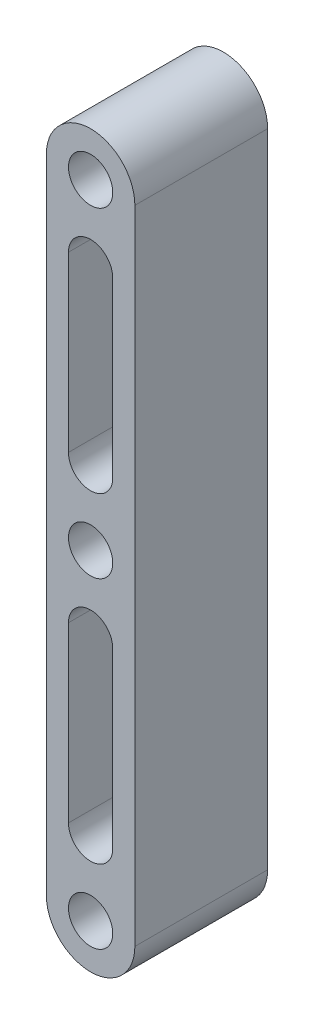
SolidWorks part; units mm, degrees
ref_plane "Front Plane" through (0, 0, 0) normal (0, 0, 1) x (1, 0, 0)
ref_plane "Top Plane" through (0, 0, 0) normal (0, 1, 0) x (1, 0, 0)
ref_plane "Right Plane" through (0, 0, 0) normal (1, 0, 0) x (0, 0, -1)
sketch "Sketch1" plane through (0, 0, 0) normal (0, 0, 1) x (1, 0, 0)
  line L0 (0, 0) -> (0, -87) construction
  line L1 (6, 0) -> (6, -87)
  line L2 (-6, 0) -> (-6, -87)
  line L3 (0, -10) -> (0, -33.5) construction
  line L4 (3, -10) -> (3, -33.5)
  line L5 (-3, -10) -> (-3, -33.5)
  line L6 (0, -53.5) -> (0, -77) construction
  line L7 (3, -53.5) -> (3, -77)
  line L8 (-3, -53.5) -> (-3, -77)
  arc A0 (6, 0) -> (-6, 0) centre (0, 0) ccw
  arc A1 (-6, -87) -> (6, -87) centre (0, -87) ccw
  circle A2 centre (0, -87) radius 3
  circle A3 centre (0, 0) radius 3
  circle A4 centre (0, -43.5) radius 3
  arc A5 (3, -10) -> (-3, -10) centre (0, -10) ccw
  arc A6 (-3, -33.5) -> (3, -33.5) centre (0, -33.5) ccw
  arc A7 (3, -53.5) -> (-3, -53.5) centre (0, -53.5) ccw
  arc A8 (-3, -77) -> (3, -77) centre (0, -77) ccw
  point P3 (0, -43.5)
  point P16 (0, -21.75)
  point P21 (0, -65.25)
  point P28 (0, 0)
  dimension "D1" = 6
  dimension "D2" = 6
  dimension "D3" = 43.5
  dimension "D4" = 10
  dimension "D5" = 10
  dimension "D6" = 10
  dimension "D7" = 10
extrude "Boss-Extrude1" add sketch "Sketch1" along normal mid plane 18
equation "\"D5@Sketch1\"=\"D4@Sketch1\""
equation "\"D6@Sketch1\"=\"D4@Sketch1\""
equation "\"D7@Sketch1\"=\"D4@Sketch1\""
